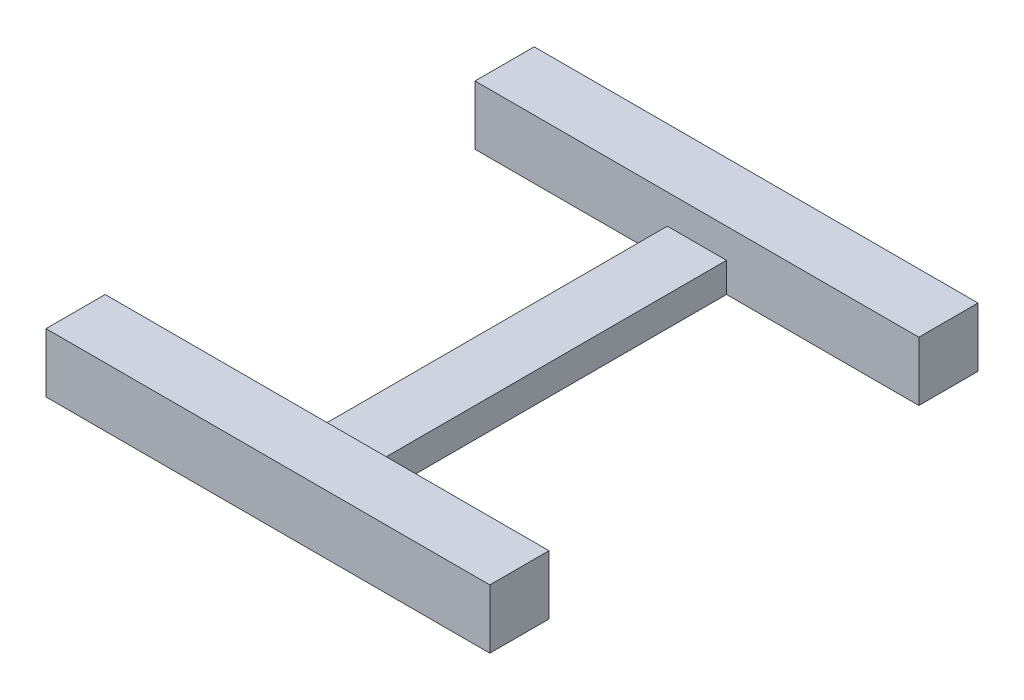
SolidWorks part; units mm, degrees
ref_plane "Front Plane" through (0, 0, 0) normal (0, 0, 1) x (1, 0, 0)
ref_plane "Top Plane" through (0, 0, 0) normal (0, 1, 0) x (1, 0, 0)
ref_plane "Right Plane" through (0, 0, 0) normal (1, 0, 0) x (0, 0, -1)
sketch "Sketch1" plane through (0, 0, 0) normal (0, 1, 0) x (1, 0, 0)
  line L0 (-15, 12.5) -> (-2, 12.5)
  line L2 (-15, -12.5) -> (-15, -16.5)
  line L3 (-15, -16.5) -> (15, -16.5)
  line L4 (15, -12.5) -> (15, -16.5)
  line L6 (-15, 12.5) -> (-15, 16.5)
  line L7 (-15, 16.5) -> (15, 16.5)
  line L8 (15, 12.5) -> (15, 16.5)
  line L9 (-2, 12.5) -> (-2, -12.5)
  line L10 (-2, -12.5) -> (-15, -12.5)
  line L11 (15, 12.5) -> (2, 12.5)
  line L12 (2, 12.5) -> (2, -12.5)
  line L13 (2, -12.5) -> (15, -12.5)
  line L15 (0, 16.5) -> (0, -16.5) construction
  line L16 (-2, 0) -> (2, 0) construction
  point P14 (-0.7046, 2.4307)
  point P17 (0.7624, 2.319)
  point P18 (0, 0)
  point P19 (0, 0)
  dimension "D1" = 4
  dimension "D2" = 33
  dimension "D3" = 4
  dimension "D4" = 30
extrude "Boss-Extrude1" add sketch "Sketch1" along normal blind 4
sketch "Sketch2" plane through (0, 4, 0) normal (0, 1, 0) x (1, 0, 0)
  line L1 (-2, -12.5) -> (2, -12.5)
  line L2 (-2, -12.5) -> (-2, 12.5)
  line L3 (-2, 12.5) -> (2, 12.5)
  line L4 (2, -12.5) -> (2, 12.5)
extrude "Cut-Extrude1" cut sketch "Sketch2" against normal blind 2
